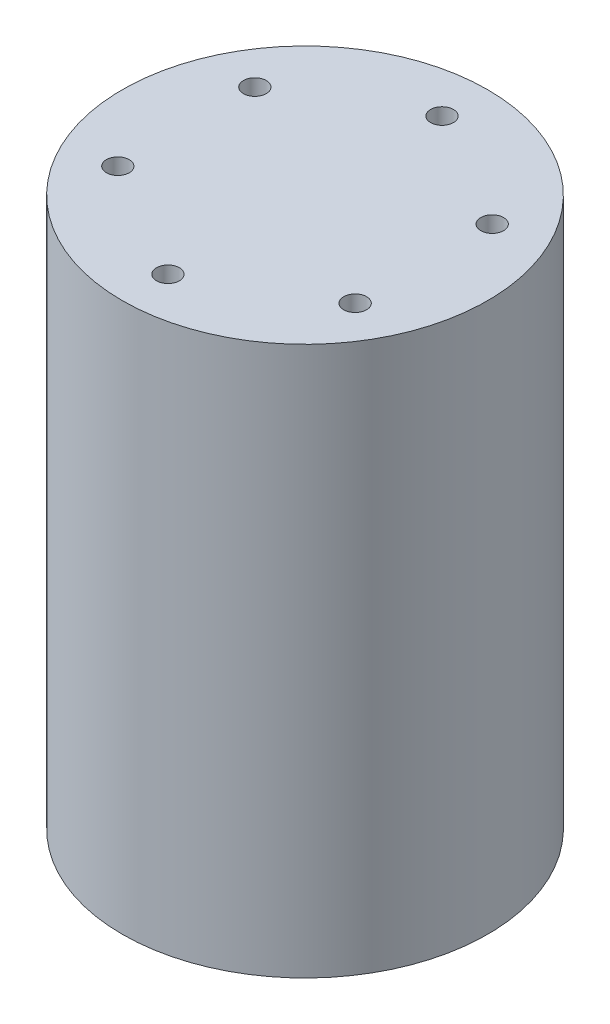
SolidWorks part; units mm, degrees
material "ABS"
ref_plane "Front Plane" through (0, 0, 0) normal (0, 0, 1) x (1, 0, 0)
ref_plane "Top Plane" through (0, 0, 0) normal (0, 1, 0) x (1, 0, 0)
ref_plane "Right Plane" through (0, 0, 0) normal (1, 0, 0) x (0, 0, -1)
sketch "Sketch1" plane through (0, 0, 0) normal (0, 1, 0) x (1, 0, 0)
  circle A0 centre (0, 0) radius 30 construction
  circle A1 centre (0, 0) radius 40
  circle A2 centre (0, 30) radius 3 construction
  circle A3 centre (25.9808, 15) radius 3 construction
  circle A4 centre (25.9808, -15) radius 3 construction
  circle A5 centre (0, -30) radius 3 construction
  circle A6 centre (-25.9808, -15) radius 3 construction
  circle A7 centre (-25.9808, 15) radius 3 construction
  point P18 (0, 0)
  dimension "D1" = 6
  dimension "D2" = 60
  dimension "D3" = 80
  dimension "D4" = 6
extrude "Boss-Extrude1" add sketch "Sketch1" along normal blind 60.075
hole_wizard "Tap Drill for M6x1.0 Tap1" positions "3DSketch2" profile "Sketch4" hole size "M6x1.0" standard "ANSI Metric"
sketch3d "3DSketch2"
  point P0 (25.9808, 0, 15)
  point P2 (25.9808, 0, -15)
  point P4 (0, 0, -30)
  point P6 (-25.9808, 0, -15)
  point P8 (-25.9808, 0, 15)
  point P10 (0, 0, 30)
sketch "Sketch4" plane through (25.9808, 0, 15) normal (1, 0, 0) x (0, 0, -1)
  line L0 (0, 0) -> (0, 11.5022)
  line L1 (0, 11.5022) -> (2.5, 10)
  line L2 (2.5, 10) -> (2.5, 0)
  line L5 (2.5, 0) -> (0, 0)
  line L10 (0, 11.5022) -> (-2.5, 10) construction
  line L11 (0, -6.35) -> (0, 107.95) construction
  dimension "Hole Dia." = 5
  dimension "Hole Depth" = 10
  dimension "Drill Angle" = 118
mirror "Mirror1" about plane through (0, 60.075, 0) normal (0, 1, 0) of "Tap Drill for M6x1.0 Tap1", "Boss-Extrude1"
